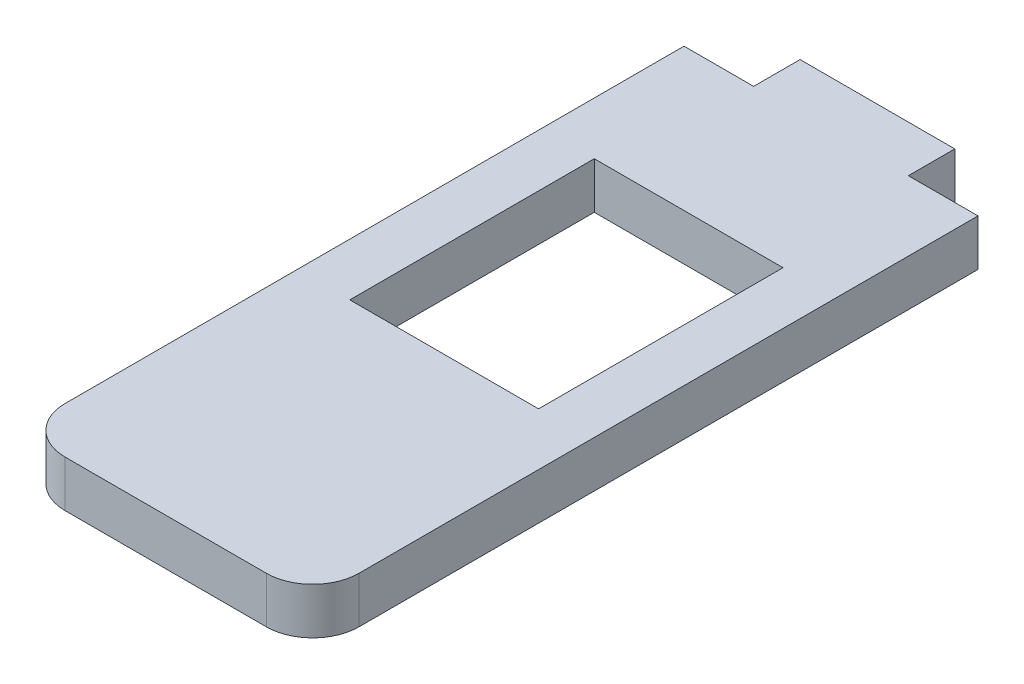
SolidWorks part; units mm, degrees
ref_plane "Plan de face" through (0, 0, 0) normal (0, 0, 1) x (1, 0, 0)
ref_plane "Plan de dessus" through (0, 0, 0) normal (0, 1, 0) x (1, 0, 0)
ref_plane "Plan de droite" through (0, 0, 0) normal (1, 0, 0) x (0, 0, -1)
sketch "Esquisse1" plane through (0, 0, 0) normal (0, 1, 0) x (1, 0, 0)
  line L0 (-9.5, 43) -> (-5, 43)
  line L1 (-6.5, 0) -> (6.5, 0)
  line L2 (-9.5, 3) -> (-9.5, 43)
  line L3 (-5, 46) -> (5, 46)
  line L4 (9.5, 3) -> (9.5, 43)
  line L5 (-5, 43) -> (-5, 46)
  line L6 (5, 46) -> (5, 43)
  line L7 (5, 43) -> (9.5, 43)
  line L8 (0, 0) -> (0, 46) construction
  line L10 (-6.1, 33.8) -> (6.1, 33.8)
  line L11 (-6.1, 33.8) -> (-6.1, 18)
  line L12 (-6.1, 18) -> (6.1, 18)
  line L13 (6.1, 33.8) -> (6.1, 18)
  arc A0 (6.5, 0) -> (9.5, 3) centre (6.5, 3) ccw
  arc A1 (-6.5, 0) -> (-9.5, 3) centre (-6.5, 3) cw
  point P9 (0, 33.8)
  point P11 (0, 46)
  point P16 (9.5, 0)
  point P19 (-9.5, 0)
  dimension "D5" = 3
  dimension "D1" = 46
  dimension "D2" = 19
  dimension "D3" = 10
  dimension "D4" = 3
  dimension "D6" = 12.2
  dimension "D7" = 15.8
  dimension "D8" = 18
extrude "Boss.-Extru.1" add sketch "Esquisse1" along normal blind 3
